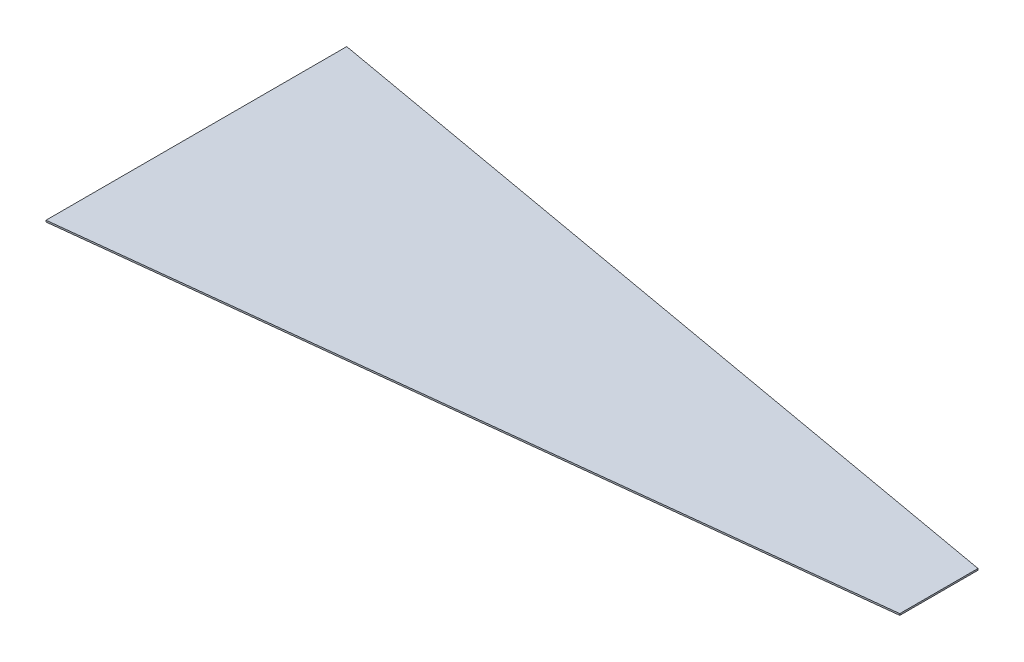
SolidWorks part; units mm, degrees
ref_plane "Front Plane" through (0, 0, 0) normal (0, 0, 1) x (1, 0, 0)
ref_plane "Top Plane" through (0, 0, 0) normal (0, 1, 0) x (1, 0, 0)
ref_plane "Right Plane" through (0, 0, 0) normal (1, 0, 0) x (0, 0, -1)
sketch "Sketch1" plane through (0, 0, 0) normal (0, 1, 0) x (1, 0, 0)
  line L0 (0, -241.3) -> (0, 241.3)
  line L1 (1231.9, 22.5411) -> (1231.9, -102.9349)
  line L2 (0, 241.3) -> (0, 120.65) construction
  line L3 (1231.9, 22.5411) -> (1231.9, -8.8279) construction
  line L4 (0, 120.65) -> (1631.7558, 120.65) construction
  line L5 (0, 120.65) -> (1231.9, -8.8279) construction
  line L6 (0, -241.3) -> (1231.9, -102.9349)
  line L7 (0, 241.3) -> (1231.9, 22.5411)
  line L9 (139.7, 216.4923) -> (139.7, -225.6091)
  point P4 (0, 0)
  dimension "D1" = 482.6
  dimension "D2" = 125.476
  dimension "D3" = 1231.9
  dimension "D4" = 120.65
  dimension "D5" = 31.369
  dimension "D6" = 6
  dimension "D7" = 139.7
  dimension "D8" = 442.1014
extrude "Boss-Extrude1" add sketch "Sketch1" along normal blind 2.54 contours L0 L7 L1 L6
equation "\"D4@Sketch1\"=\"D1@Sketch1\"/4"
equation "\"D5@Sketch1\"=\"D2@Sketch1\"/4"
